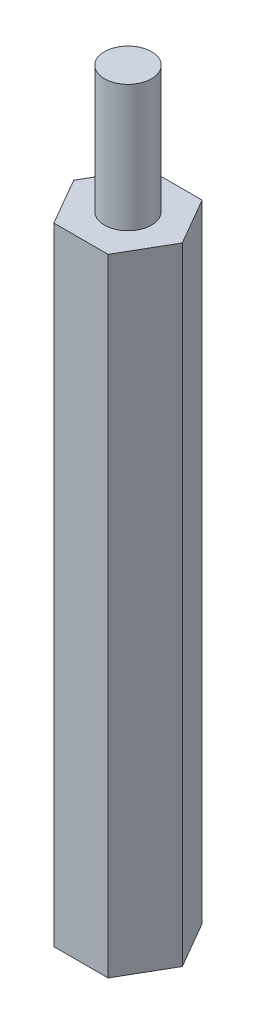
SolidWorks part; units mm, degrees
ref_plane "Front Plane" through (0, 0, 0) normal (0, 0, 1) x (1, 0, 0)
ref_plane "Top Plane" through (0, 0, 0) normal (0, 1, 0) x (1, 0, 0)
ref_plane "Right Plane" through (0, 0, 0) normal (1, 0, 0) x (0, 0, -1)
sketch "Sketch3" plane through (0, 0, 0) normal (0, 1, 0) x (1, 0, 0)
  line L1 (-3.4641, 0) -> (-1.7321, -3)
  line L2 (-1.7321, -3) -> (1.7321, -3)
  line L3 (1.7321, -3) -> (3.4641, 0)
  line L4 (3.4641, 0) -> (1.7321, 3)
  line L5 (1.7321, 3) -> (-1.7321, 3)
  line L6 (-1.7321, 3) -> (-3.4641, 0)
  circle A0 centre (0, 0) radius 3 construction
  dimension "D1" = 6
extrude "Boss-Extrude1" add sketch "Sketch3" along normal blind 40
sketch "Sketch5" plane through (0, 40, 0) normal (0, 1, 0) x (1, 0, 0)
  circle A0 centre (0, 0) radius 1.5
  dimension "D1" = 3
extrude "Boss-Extrude2" add sketch "Sketch5" along normal blind 8.0916
sketch "Sketch6" plane through (0, 0, 0) normal (0, -1, 0) x (1, 0, 0)
  circle A0 centre (0, 0) radius 1.5
extrude "Cut-Extrude1" cut sketch "Sketch6" against normal blind 4
